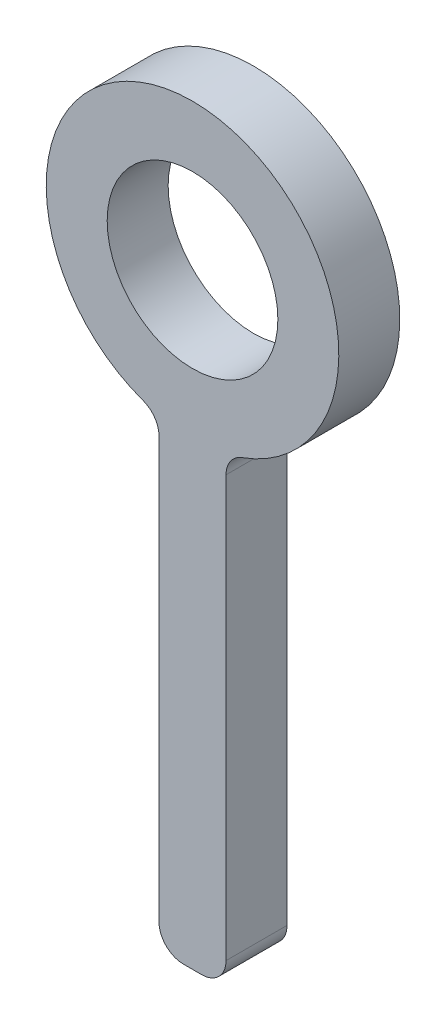
SolidWorks part; units mm, degrees
ref_plane "Front Plane" through (0, 0, 0) normal (0, 0, 1) x (1, 0, 0)
ref_plane "Top Plane" through (0, 0, 0) normal (0, 1, 0) x (1, 0, 0)
ref_plane "Right Plane" through (0, 0, 0) normal (1, 0, 0) x (0, 0, -1)
sketch "Sketch1" plane through (0, 0, 0) normal (0, 0, 1) x (1, 0, 0)
  line L0 (0, 0) -> (0, -38)
  line L1 (0, -38) -> (5.5, -38)
  line L2 (5.5, -38) -> (5.5, 0)
  arc A0 (0, 0) -> (5.5, 0) centre (2.75, 11.6806) cw
  circle A1 centre (2.75, 11.6806) radius 7
  dimension "D3" = 12
  dimension "D4" = 5
  dimension "D1" = 5.5
  dimension "D2" = 38
extrude "Boss-Extrude1" add sketch "Sketch1" along normal blind 5
fillet "Fillet1" radius 2 4 edges at (0, 0, 2.5) (5.5, 0, 2.5) (5.5, -38, 2.5) (0, -38, 2.5)
